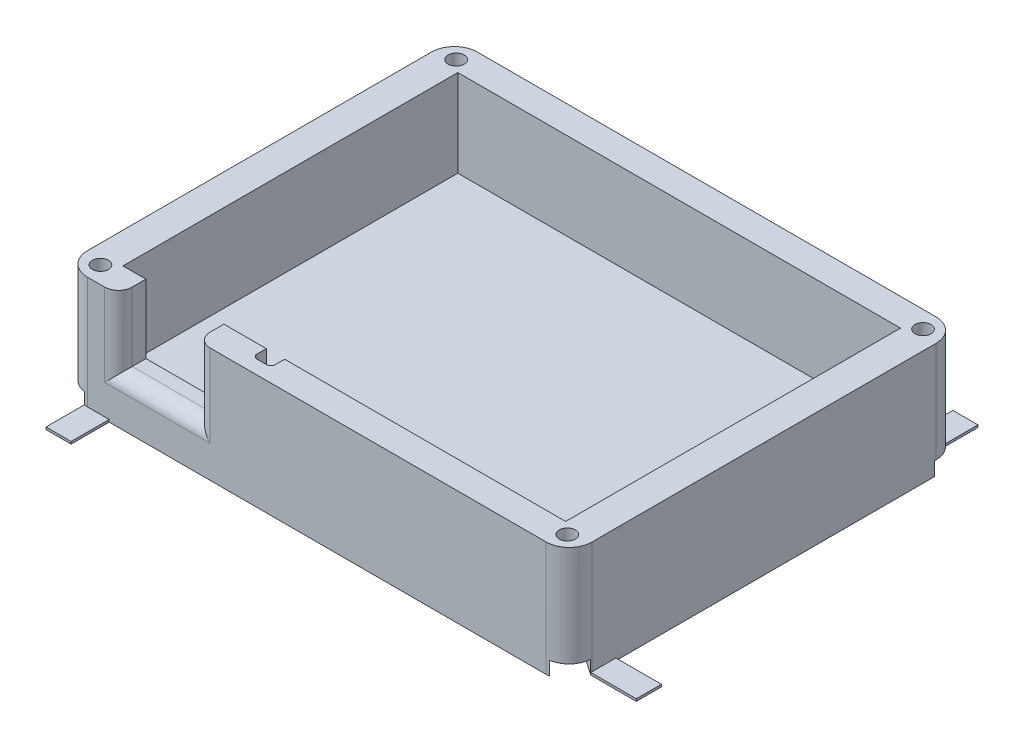
SolidWorks part; units mm, degrees
ref_plane "Front Plane" through (0, 0, 0) normal (0, 0, 1) x (1, 0, 0)
ref_plane "Top Plane" through (0, 0, 0) normal (0, 1, 0) x (1, 0, 0)
ref_plane "Right Plane" through (0, 0, 0) normal (1, 0, 0) x (0, 0, -1)
sketch "Sketch1" plane through (0, 0, 0) normal (0, 1, 0) x (1, 0, 0)
  line L1 (-55, 42.5) -> (55, 42.5)
  line L2 (-55, 42.5) -> (-55, -42.5)
  line L3 (-55, -42.5) -> (55, -42.5)
  line L4 (55, 42.5) -> (55, -42.5)
  line L5 (-55, 42.5) -> (55, -42.5) construction
  line L6 (-55, -42.5) -> (55, 42.5) construction
  point P0 (0, 0)
  dimension "D1" = 85
  dimension "D2" = 110
extrude "Base" add sketch "Sketch1" along normal blind 25
fillet "Fillet1" radius 5 4 edges at (-55, 12.5, -42.5) (55, 12.5, 42.5) (55, 12.5, -42.5) (-55, 12.5, 42.5)
sketch "Sketch2" plane through (0, 25, 0) normal (0, 1, 0) x (1, 0, 0)
  line L1 (-48.25, 36.5) -> (48.25, 36.5)
  line L2 (-48.25, 36.5) -> (-48.25, -36.5)
  line L3 (-48.25, -36.5) -> (48.25, -36.5)
  line L4 (48.25, 36.5) -> (48.25, -36.5)
  line L5 (-48.25, 36.5) -> (48.25, -36.5) construction
  line L6 (-48.25, -36.5) -> (48.25, 36.5) construction
  point P0 (0, 0)
  dimension "D1" = 73
  dimension "D2" = 96.5
extrude "Basket" cut sketch "Sketch2" against normal blind 19
sketch "Sketch3" plane through (0, 25, 0) normal (0, 1, 0) x (1, 0, 0)
  line L0 (-55, -12.0792) -> (-15, -12.0792) construction
  line L1 (-55, 37.5) -> (-55, -37.5) construction
  line L2 (-15, -12.0792) -> (-15, -36.5) construction
  line L3 (-48.25, -36.5) -> (48.25, -36.5) construction
  line L4 (-48.25, 36.5) -> (-48.25, -36.5) construction
  line L5 (-17, -33.5) -> (-13, -33.5)
  line L6 (-17, -33.5) -> (-17, -39.5)
  line L7 (-17, -39.5) -> (-13, -39.5)
  line L8 (-13, -33.5) -> (-13, -39.5)
  line L9 (-17, -33.5) -> (-13, -39.5) construction
  line L10 (-17, -39.5) -> (-13, -33.5) construction
  dimension "D2" = 4
  dimension "D3" = 6
  dimension "D4" = 33.25
extrude "Wire Channel" cut sketch "Sketch3" against normal up to surface (19 mm away) up to face at (0, 6, 0)
fillet "Wire Channel Rounding" radius 1 2 edges at (-13, 15.5, 39.5) (-17, 15.5, 39.5)
ref_plane "Battery Pack Left Side Wall" through (-48.25, 0, 0) normal (1, 0, 0) x (0, 0, -1)
sketch "Sketch5" plane through (0, 0, 42.5) normal (0, 0, 1) x (1, 0, 0)
  line L0 (-48.25, 25) -> (-43.25, 25) construction
  line L1 (-48.25, -9.9) -> (-48.25, 9.9) construction
  line L2 (-50, 25) -> (50, 25) construction
  line L5 (-43.25, 25) -> (-26.25, 25)
  line L6 (-43.25, 25) -> (-43.25, 10)
  line L7 (-43.25, 10) -> (-26.25, 10)
  line L8 (-26.25, 25) -> (-26.25, 10)
  dimension "D1" = 5
  dimension "D3" = 17
  dimension "D4" = 15
extrude "Switch Cut-out" cut sketch "Sketch5" against normal up to next
fillet "Switch Cut-out Rounding" radius 3 3 edges at (-43.25, 17.5, 42.5) (-34.75, 10, 42.5) (-26.25, 17.5, 42.5)
sketch "Sketch14" plane through (0, 25, 0) normal (0, 1, 0) x (1, 0, 0)
  line L0 (-53.5355, 41.0355) -> (-48.25, 36.5) construction
  line L1 (53.5355, 41.0355) -> (48.25, 36.5) construction
  line L2 (53.5355, -41.0355) -> (48.25, -36.5) construction
  line L3 (-53.5355, -41.0355) -> (-48.25, -36.5) construction
  arc A0 (-50, 42.5) -> (-55, 37.5) centre (-50, 37.5) ccw construction
  arc A1 (55, 37.5) -> (50, 42.5) centre (50, 37.5) ccw construction
  arc A2 (50, -42.5) -> (55, -37.5) centre (50, -37.5) ccw construction
  arc A3 (-55, -37.5) -> (-50, -42.5) centre (-50, -37.5) ccw construction
  circle A4 centre (-50.8928, 38.7678) radius 1.75
  circle A5 centre (50.8928, 38.7678) radius 1.75
  circle A6 centre (50.8928, -38.7678) radius 1.75
  circle A7 centre (-50.8928, -38.7678) radius 1.75
  dimension "D1" = 3.5
  dimension "D2" = 77.5355
  dimension "D3" = 101.7855
extrude "Corner Holes" cut sketch "Sketch14" against normal through all
sketch "Sketch15" plane through (0, 0, 0) normal (0, -1, 0) x (1, 0, 0)
  line L0 (-50.641, 42.3885) -> (-52.1783, 43.4161)
  line L1 (-47.6302, 40.3758) -> (-50.641, 42.3885)
  line L2 (50.596, 42.3929) -> (52.0915, 43.4278)
  line L3 (47.9017, 36.6981) -> (51.1896, 35.1426)
  line L4 (-54.1438, 37.152) -> (-51.1314, 35.1383)
  line L5 (-51.1314, 35.1383) -> (-47.8689, 36.7464)
  line L6 (-47.8689, 36.7464) -> (-47.6302, 40.3758)
  line L7 (-52.1783, 43.4161) -> (-55.727, 38.1074)
  line L8 (-55.727, 38.1074) -> (-54.1438, 37.152)
  line L9 (51.1896, 35.1426) -> (54.1807, 37.2122)
  line L10 (-50.5474, 42.4498) -> (-53.8646, 40.8148) [skipped]
  line L11 (-53.9089, 40.9079) -> (-54.1515, 37.2176) [skipped]
  line L12 (54.1678, -36.6991) -> (55.7428, -37.6084)
  line L13 (54.1678, -36.6991) -> (50.8928, -34.8083)
  line L14 (54.1807, 37.2122) -> (53.8839, 40.8374) construction
  line L15 (53.8839, 40.8374) -> (50.596, 42.3929) construction
  line L16 (50.596, 42.3929) -> (47.6049, 40.3233)
  line L17 (47.6049, 40.3233) -> (47.9017, 36.6981)
  line L18 (50.8928, -34.8083) -> (47.4638, -36.788)
  line L19 (52.0915, 43.4278) -> (55.6762, 38.247)
  line L20 (55.6762, 38.247) -> (54.1807, 37.2122)
  line L21 (47.4638, -36.788) -> (47.4638, -40.7475)
  line L22 (47.4638, -40.7475) -> (50.7388, -42.6383)
  line L23 (-53.9527, -36.8014) -> (-55.5692, -37.6348)
  line L24 (-53.9527, -36.8014) -> (-54.1257, -40.4346) construction
  line L25 (55.7428, -37.6084) -> (52.3138, -43.5477)
  line L26 (52.3138, -43.5477) -> (50.7388, -42.6383)
  line L27 (-54.1257, -40.4346) -> (-51.0657, -42.401) construction
  line L28 (54.3218, -39.981) -> (54.3218, -36.3437) [skipped]
  line L29 (51.5566, -42.344) -> (54.7066, -40.5253) [skipped]
  line L30 (-51.0657, -42.401) -> (-47.8328, -40.7341)
  line L31 (-47.8328, -40.7341) -> (-47.6599, -37.1009)
  line L32 (-47.6599, -37.1009) -> (-50.7198, -35.1346)
  line L33 (-50.7198, -35.1346) -> (-53.9527, -36.8014)
  line L34 (-55.5692, -37.6348) -> (-52.6822, -43.2344)
  line L35 (-52.6822, -43.2344) -> (-51.0657, -42.401)
  circle A0 centre (-50.8928, 38.7678) radius 3.15 construction
  circle A1 centre (50.8928, 38.7678) radius 3.15 construction
  circle A2 centre (50.8928, -38.7678) radius 3.429 construction
  circle A3 centre (-50.8928, -38.7678) radius 3.15 construction
  dimension "D1" = 6.3
  dimension "D2" = 6.3
  dimension "D3" = 6.3
extrude "Bottom Nut Cut-out" cut sketch "Sketch15" against normal blind 3
sketch "Sketch18" plane through (0, 0, 0) normal (0, -1, 0) x (1, 0, 0)
  line L0 (-50.7281, 42.4467) -> (-50.7281, 50.8043)
  line L1 (-50.7281, 50.8043) -> (-45.2548, 50.8043)
  line L2 (-45.2548, 50.8043) -> (-45.2548, 42.5)
  line L3 (-50, 42.5) -> (50, 42.5) construction
  line L4 (-45.2548, 42.5) -> (-50.7281, 42.4467)
  line L5 (54.9925, 37.7739) -> (64.9274, 37.7739)
  line L6 (64.9274, 37.7739) -> (64.9274, 32.3007)
  line L7 (64.9274, 32.3007) -> (55, 32.3007)
  line L8 (55, 37.5) -> (55, -37.1796) construction
  line L9 (55, 32.3007) -> (54.9925, 37.7739)
  line L10 (50.4621, -42.4786) -> (50.4621, -51.1818)
  line L11 (50.4621, -51.1818) -> (44.9888, -51.1818)
  line L12 (44.9888, -51.1818) -> (44.9888, -42.5)
  line L13 (50, -42.5) -> (-50, -42.5) construction
  line L14 (44.9888, -42.5) -> (50.4621, -42.4786)
  line L15 (-55, -37.3414) -> (-63.3043, -37.3414)
  line L16 (-63.3043, -37.3414) -> (-63.3043, -31.8681)
  line L17 (-63.3043, -31.8681) -> (-55, -31.8681)
  line L18 (-55, -37.3414) -> (-55, 37.5) construction
  line L19 (-55, -31.8681) -> (-55, -37.3414)
extrude "Printing Tie-downs" add sketch "Sketch18" against normal blind 0.5
